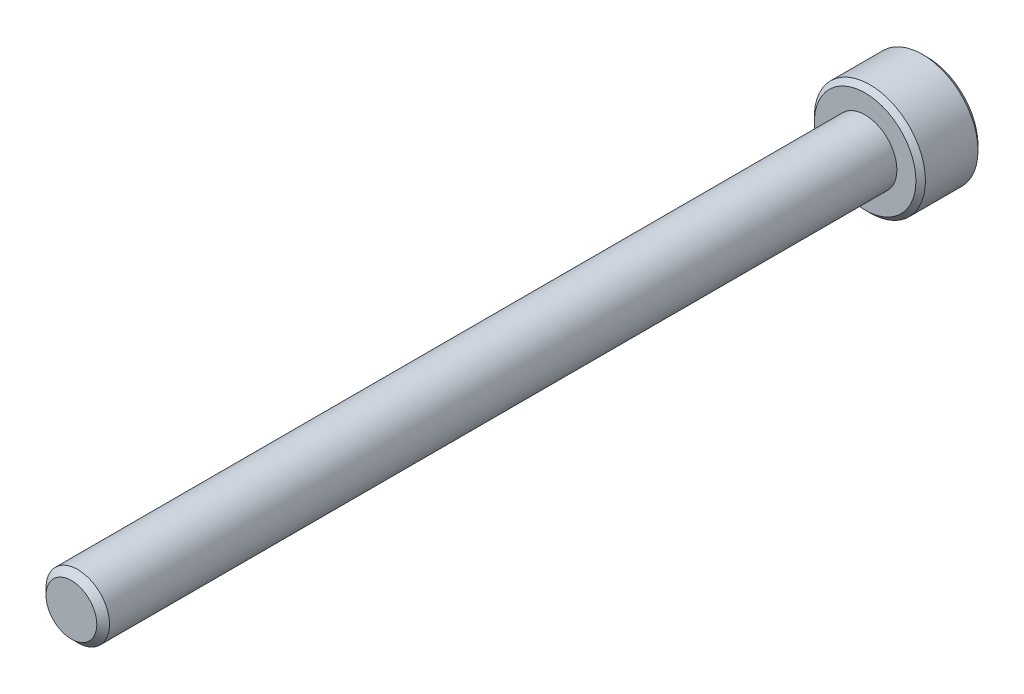
SolidWorks part; units mm, degrees
material "AISI 304"
ref_plane "前视基准面" through (0, 0, 0) normal (0, 0, 1) x (1, 0, 0)
ref_plane "上视基准面" through (0, 0, 0) normal (0, 1, 0) x (1, 0, 0)
ref_plane "右视基准面" through (0, 0, 0) normal (1, 0, 0) x (0, 0, -1)
sketch "草图1" plane through (0, 0, 0) normal (0, 0, 1) x (1, 0, 0)
  circle A0 centre (0, 0) radius 3.5
  dimension "D1" = 7
extrude "凸台-拉伸1" add sketch "草图1" along normal blind 3.91
sketch "草图2" plane through (0, 0, 3.91) normal (0, 0, 1) x (1, 0, 0)
  circle A0 centre (0, 0) radius 2
  dimension "D1" = 4
extrude "凸台-拉伸2" add sketch "草图2" along normal blind 50
sketch "草图3" plane through (0, 0, 0) normal (0, 0, -1) x (-1, 0, 0)
  line L1 (0, 1.7609) -> (-1.525, 0.8805)
  line L2 (-1.525, 0.8805) -> (-1.525, -0.8805)
  line L3 (-1.525, -0.8805) -> (0, -1.7609)
  line L4 (0, -1.7609) -> (1.525, -0.8805)
  line L5 (1.525, -0.8805) -> (1.525, 0.8805)
  line L6 (1.525, 0.8805) -> (0, 1.7609)
  circle A0 centre (0, 0) radius 1.525 construction
  dimension "D1" = 3.05
extrude "切除-拉伸1" cut sketch "草图3" against normal blind 2
chamfer "倒角1" distance 0.4 angle 45 1 edges at (2, 0, 53.91)
chamfer "倒角2" distance 0.3 angle 45 2 edges at (3.5, 0, 3.91) (3.5, 0, 0)
